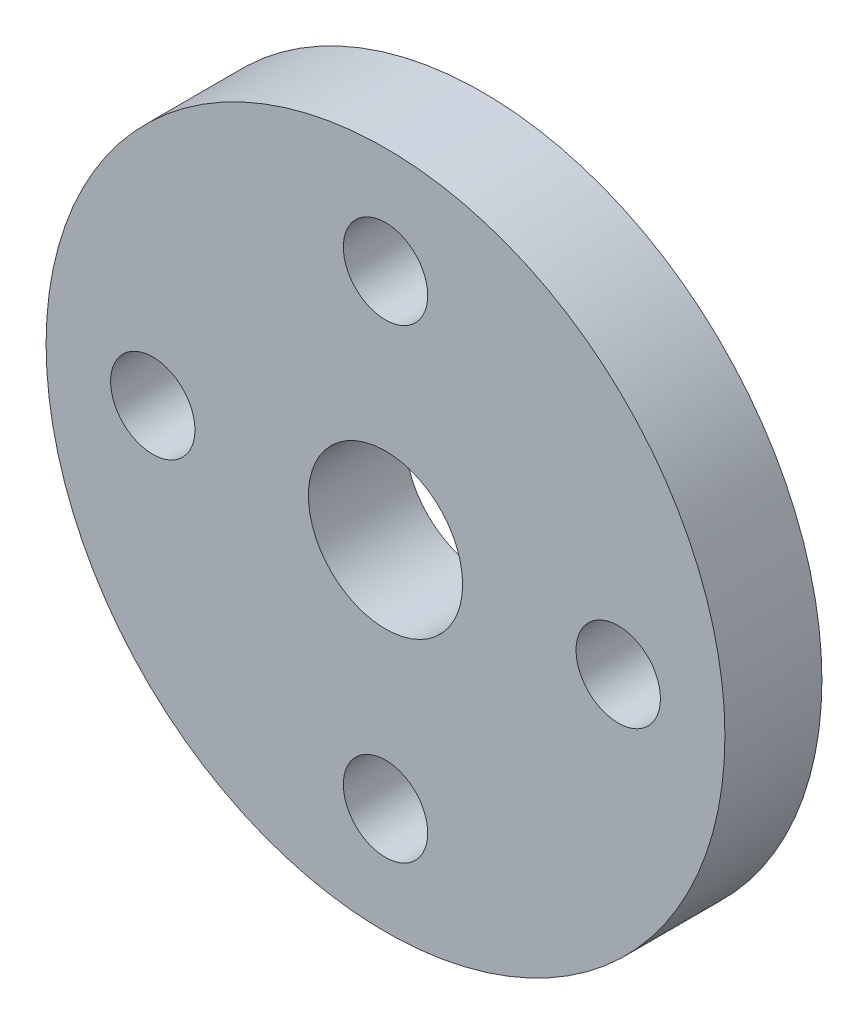
SolidWorks part; units mm, degrees
ref_plane "Front Plane" through (0, 0, 0) normal (0, 0, 1) x (1, 0, 0)
ref_plane "Top Plane" through (0, 0, 0) normal (0, 1, 0) x (1, 0, 0)
ref_plane "Right Plane" through (0, 0, 0) normal (1, 0, 0) x (0, 0, -1)
sketch "Sketch1" plane through (0, 0, 0) normal (0, 0, 1) x (1, 0, 0)
  circle A0 centre (0, 0) radius 17.5
  circle A2 centre (12, 0) radius 2.175
  circle A3 centre (0, 12) radius 2.175
  circle A4 centre (-12, 0) radius 2.175
  circle A5 centre (0, -12) radius 2.175
  circle A6 centre (0, 0) radius 3.975
  dimension "D1" = 4.35
  dimension "D2" = 4.35
  dimension "D3" = 4.35
  dimension "D4" = 4.35
  dimension "D5" = 7.95
extrude "Boss-Extrude1" add sketch "Sketch1" along normal blind 5
